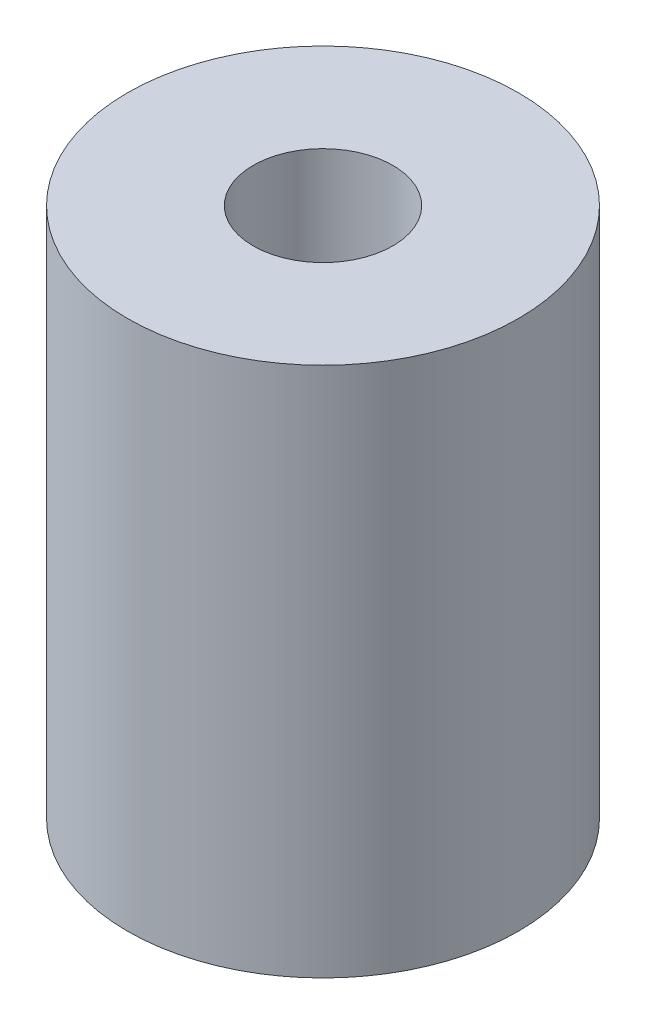
SolidWorks part; units mm, degrees
ref_plane "Front Plane" through (0, 0, 0) normal (0, 0, 1) x (1, 0, 0)
ref_plane "Top Plane" through (0, 0, 0) normal (0, 1, 0) x (1, 0, 0)
ref_plane "Right Plane" through (0, 0, 0) normal (1, 0, 0) x (0, 0, -1)
sketch "Sketch1" plane through (0, 0, 0) normal (0, 1, 0) x (1, 0, 0)
  circle A0 centre (0, 0) radius 2.5
  circle A1 centre (0, 0) radius 7
extrude "Boss-Extrude1" add sketch "Sketch1" along normal blind 19
